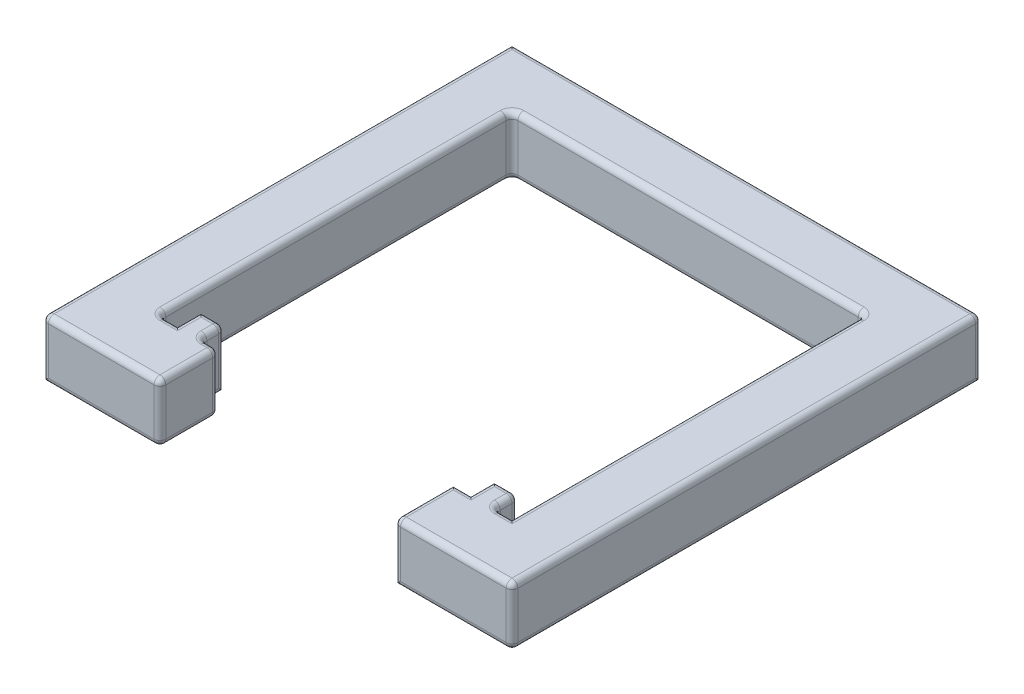
SolidWorks part; units mm, degrees
ref_plane "Front Plane" through (0, 0, 0) normal (0, 0, 1) x (1, 0, 0)
ref_plane "Top Plane" through (0, 0, 0) normal (0, 1, 0) x (1, 0, 0)
ref_plane "Right Plane" through (0, 0, 0) normal (1, 0, 0) x (0, 0, -1)
sketch "Sketch1" plane through (0, 0, 0) normal (0, 1, 0) x (1, 0, 0)
  line L9 (-61.1123, -370.9875) -> (-53.42, -370.9875)
  line L10 (-61.1123, -370.9875) -> (-61.1123, -410.9875)
  line L11 (-61.1123, -410.9875) -> (-56.1123, -410.9875)
  line L12 (-56.1123, -375.9875) -> (-56.1123, -405.9875)
  line L13 (-61.1123, -370.9875) -> (-21.1123, -370.9875)
  line L14 (-61.1123, -370.9875) -> (-61.1123, -219.2785)
  line L15 (-56.1123, -375.9875) -> (-26.1123, -375.9875)
  line L16 (-21.1123, -370.9875) -> (-21.1123, -219.2785)
  line L17 (214.9573, -370.9875) -> (-21.1123, -370.9875)
  line L18 (-26.1123, -375.9875) -> (-26.1123, -405.9875)
  line L19 (-26.1123, -410.9875) -> (-21.1123, -410.9875)
  line L20 (-21.1123, -370.9875) -> (-21.1123, -410.9875)
  line L22 (-56.1123, -405.9875) -> (-56.1123, -410.9875)
  line L26 (-26.1123, -405.9875) -> (-26.1123, -410.9875)
  line L27 (-26.1123, -410.9875) -> (-31.1123, -410.9875)
  line L28 (-56.1123, -405.9875) -> (-51.1123, -405.9875)
  line L29 (-61.1123, -380.152) -> (-61.1123, -410.9875)
  line L30 (-61.1123, -410.9875) -> (-51.1123, -410.9875)
  line L31 (-51.1123, -405.9875) -> (-51.1123, -410.9875)
  line L32 (-31.1123, -405.9875) -> (-26.1123, -405.9875)
  line L33 (-31.1123, -405.9875) -> (-31.1123, -410.9875)
  line L34 (-31.1123, -410.9875) -> (-21.1123, -410.9875)
  line L35 (-21.1123, -380.152) -> (-21.1123, -410.9875)
  line L36 (-54.6123, -403.9875) -> (-52.6123, -403.9875)
  line L37 (-54.6123, -403.9875) -> (-54.6123, -405.9875)
  line L38 (-54.6123, -405.9875) -> (-52.6123, -405.9875)
  line L39 (-52.6123, -403.9875) -> (-52.6123, -405.9875)
  line L40 (-29.6123, -403.9875) -> (-27.6123, -403.9875)
  line L41 (-29.6123, -403.9875) -> (-29.6123, -405.9875)
  line L42 (-29.6123, -405.9875) -> (-27.6123, -405.9875)
  line L43 (-27.6123, -403.9875) -> (-27.6123, -405.9875)
  point P19 (-51.1123, -408.4875)
  dimension "D1" = 20
  dimension "D2" = 5
  dimension "D3" = 5
  dimension "D4" = 5
  dimension "D5" = 5
  dimension "D6" = 5
  dimension "D7" = 5
  dimension "D8" = 5
  dimension "D9" = 30
  dimension "D10" = 30
  dimension "D11" = 2
  dimension "D12" = 1.5
  dimension "D13" = 2
  dimension "D14" = 2
  dimension "D15" = 1.5
  dimension "D16" = 2
extrude "Boss-Extrude1" add sketch "Sketch1" along normal blind 5 contours L18 L26 L19 L20 L16 L13 L9 L10 L11 L22 L12 L15 | L32 L33 L27 L26 | L31 L28 L22 L30 | L39 L36 L37 L28 | L43 L40 L41 L32
fillet "Fillet1" radius 0.5 45 edges at (-26.8623, 0, 405.9875) (-26.8623, 5, 405.9875) (-51.8623, 0, 405.9875) (-51.8623, 5, 405.9875) (-55.3623, 0, 405.9875) (-55.3623, 5, 405.9875) (-26.1123, 0, 390.9875) (-26.1123, 5, 390.9875) (-27.6123, 0, 404.9875) (-27.6123, 5, 404.9875) (-26.1123, 0, 410.9875) (-26.1123, 5, 410.9875) (-21.1123, 0, 390.9875) (-21.1123, 5, 390.9875) (-56.1123, 0, 410.9875) (-56.1123, 5, 410.9875) (-51.1123, 0, 408.4875) (-51.1123, 5, 408.4875) (-52.6123, 0, 404.9875) (-52.6123, 5, 404.9875) (-56.1123, 0, 390.9875) (-56.1123, 5, 390.9875) (-41.1123, 0, 375.9875) (-41.1123, 5, 375.9875) (-28.6123, 5, 403.9875) (-29.6123, 5, 404.9875) (-30.3623, 5, 405.9875) (-31.1123, 5, 408.4875) (-41.1123, 5, 370.9875) (-61.1123, 5, 390.9875) (-53.6123, 5, 403.9875) (-54.6123, 5, 404.9875) (-26.1123, 2.5, 375.9875) (-56.1123, 2.5, 375.9875) (-56.1123, 2.5, 405.9875) (-52.6123, 2.5, 403.9875) (-52.6123, 2.5, 405.9875) (-51.1123, 2.5, 405.9875) (-51.1123, 2.5, 410.9875) (-61.1123, 2.5, 410.9875) (-21.1123, 2.5, 370.9875) (-21.1123, 2.5, 410.9875) (-31.1123, 2.5, 410.9875) (-27.6123, 2.5, 403.9875) (-27.6123, 2.5, 405.9875)
equation "\"ScannerWidth\"= 80"
equation "\"ScannerLength\"= 40"
equation "\"SpineLength\"= 10"
equation "\"ScannerThickness\"= 5"
equation "\"ScannerHeight\" = 5"
equation "\"SpineWidth\"= 10"
equation "\"TrainWidth\"= 4"
equation "\"TrainLength\"=2"
equation "\"Armwidth\"= 5"
equation "\"Armlength\"=100"
equation "\"RailWidth\"= 2"
equation "\"RailLength\"= 65"
equation "\"RailDepth\"=2"
equation "\"HeadTowerHeight\"= 45"
equation "\"HeadSeparation\"= 20"
equation "\"HeadTowerRingRailWidth\"= 2"
equation "\"HeadTowerRingRailDepth\"= 2"
equation "\"D1@Sketch1\"=\"HeadSeparation\""
equation "\"D2@Sketch1\"=\"ScannerThickness\""
equation "\"D3@Sketch1\"=\"ScannerThickness\""
equation "\"D4@Sketch1\"=\"ScannerThickness\""
equation "\"D5@Sketch1\"=\"ScannerThickness\""
equation "\"D6@Sketch1\"=\"ScannerThickness\""
equation "\"D7@Sketch1\"=\"ScannerThickness\""
equation "\"D8@Sketch1\"=\"ScannerThickness\""
equation "\"HeadLength\"= 30"
equation "\"D9@Sketch1\"=\"HeadLength\""
equation "\"D10@Sketch1\"=\"HeadLength\""
equation "\"D11@Sketch1\"=\"HeadTowerRingRailWidth\""
equation "\"D12@Sketch1\"=(\"ScannerThickness\"-\"HeadTowerRingRailWidth\")/2"
equation "\"D13@Sketch1\"=\"HeadTowerRingRailDepth\""
equation "\"D14@Sketch1\"=\"HeadTowerRingRailWidth\""
equation "\"D15@Sketch1\"=(\"ScannerThickness\"-\"HeadTowerRingRailWidth\")/2"
equation "\"D16@Sketch1\"=\"HeadTowerRingRailDepth\""
equation "\"HeadScannerHeight\"=5"
equation "\"D1@Boss-Extrude1\"=\"HeadScannerHeight\""
